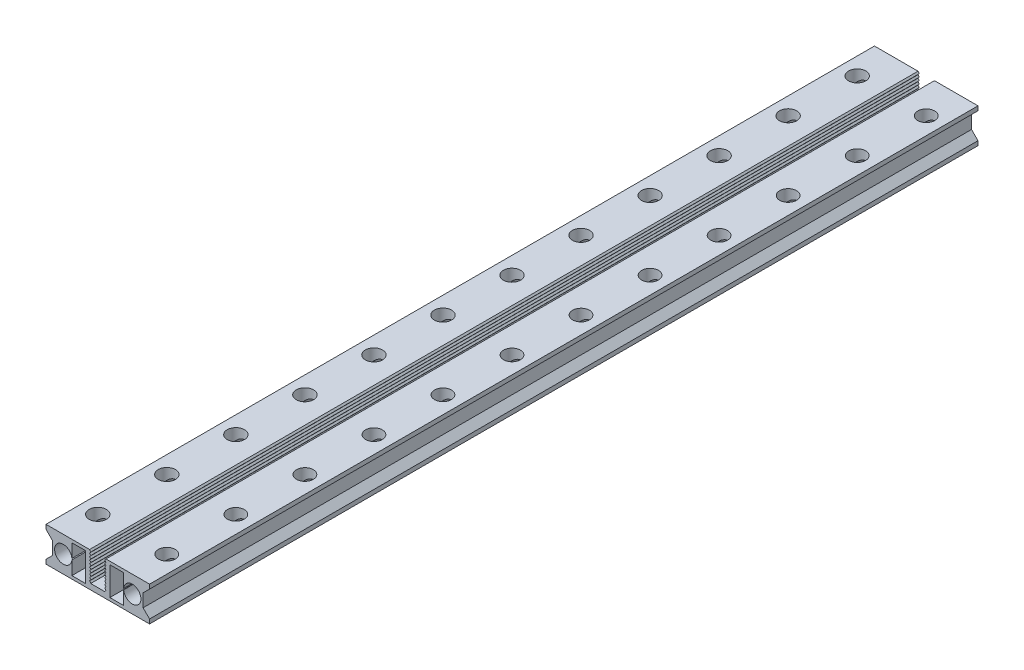
SolidWorks part; units mm, degrees
ref_plane "前视基准面" through (0, 0, 0) normal (0, 0, 1) x (1, 0, 0)
ref_plane "上视基准面" through (0, 0, 0) normal (0, 1, 0) x (1, 0, 0)
ref_plane "右视基准面" through (0, 0, 0) normal (1, 0, 0) x (0, 0, -1)
sketch "草图1" plane through (0, 0, 0) normal (0, 0, 1) x (1, 0, 0)
  line L0 (-12, 8) -> (-12, 7)
  line L1 (-12, 7) -> (-10.5, 5.5)
  line L2 (-10.5, 5.5) -> (-10.5, 2.5)
  line L3 (-10.5, 2.5) -> (-12, 1)
  line L4 (-12, 1) -> (-12, 0)
  line L5 (-12, 0) -> (12, 0)
  line L6 (12, 0) -> (12, 1)
  line L7 (12, 1) -> (10.5, 2.5)
  line L8 (10.5, 2.5) -> (10.5, 5.5)
  line L9 (10.5, 5.5) -> (12, 7)
  line L10 (12, 7) -> (12, 8)
  line L11 (12, 8) -> (1.9, 8)
  line L12 (0, 0) -> (0, 8) construction
  line L13 (-8, 4) -> (8, 4) construction
  line L14 (-1.9, 8) -> (-1.9, 1.3)
  line L15 (-6.005, 7.3) -> (-2.8, 7.3)
  line L16 (-6.005, 7.3) -> (-6.005, 4.1413)
  line L17 (-6.005, 0.7) -> (-2.8, 0.7)
  line L18 (-2.8, 7.3) -> (-2.8, 0.7)
  line L19 (-1.9, 1.3) -> (1.9, 1.3)
  line L20 (1.9, 1.3) -> (1.9, 8)
  line L21 (-1.9, 8) -> (-12, 8)
  line L22 (-6.005, 3.8587) -> (-6.005, 0.7)
  line L23 (2.8, 7.3) -> (6.005, 7.3)
  line L24 (2.8, 7.3) -> (2.8, 0.7)
  line L25 (2.8, 0.7) -> (6.005, 0.7)
  line L26 (6.005, 7.3) -> (6.005, 4.1413)
  line L27 (6.005, 3.8587) -> (6.005, 0.7)
  arc A0 (-6.005, 4.1413) -> (-6, 4) centre (-8, 4) ccw
  arc A1 (6.005, 3.8587) -> (6.005, 4.1413) centre (8, 4) ccw
  point P19 (10.5, 4)
  point P24 (-2.8, 4)
  point P27 (0, 1.3)
  dimension "D4" = 4
  dimension "D1" = 24
  dimension "D2" = 8
  dimension "D3" = 45
  dimension "D5" = 16
  dimension "D6" = 8
  dimension "D7" = 3
  dimension "D8" = 1
  dimension "D9" = 4
  dimension "D10" = 3.8
  dimension "D11" = 1.3
  dimension "D12" = 5.6
  dimension "D13" = 2.8
  dimension "D14" = 12.01
  dimension "D15" = 0.7
extrude "凸台-拉伸2" add sketch "草图1" along normal blind 192 contours L14 L21 L0 L1 L2 L3 L4 L5 L6 L7 L8 L9 L10 L11 L20 L19 A1 L27 L25 L24 L23 L26 A0 L16 L15 L18 L17 L22
sketch "草图3" plane through (0, 0, 192) normal (0, 0, 1) x (1, 0, 0)
  line L0 (-1.9, 8) -> (-1.6, 7.65)
  line L1 (-1.6, 7.65) -> (-1.9, 7.3)
  line L2 (-1.9, 8) -> (-1.9, 1.3) construction
  line L3 (-1.9, 7.3) -> (-1.9, 8)
  point P7 (-1.9, 7.65)
  dimension "D1" = 0.7
  dimension "D2" = 0.3
extrude "凸台-拉伸3" add sketch "草图3" against normal up to surface (192 mm away) up to face at (5.6025, 4, 0)
pattern_linear "阵列(线性)1" count 10 spacing 0.7 along (0, -1, 0) of "凸台-拉伸3"
mirror "镜向1" about plane through (0, 0, 0) normal (1, 0, 0) of "阵列(线性)1", "凸台-拉伸3"
sketch "草图4" plane through (0, 8, 0) normal (0, 1, 0) x (1, 0, 0)
  line L1 (12, 0) -> (1.9, 0) construction
  circle A0 centre (-8, -8) radius 2
  circle A1 centre (8, -8) radius 1.95
  dimension "D1" = 16
  dimension "D4" = 3.9
  dimension "D5" = 4
  dimension "D2" = 8
  dimension "D3" = 8
extrude "切除-拉伸1" cut sketch "草图4" against normal through all
pattern_linear "阵列(线性)2" count 12 spacing 16 along (0, 0, 1) of "切除-拉伸1"
equation "\"D13@草图1\"=\"D12@草图1\"/2"
